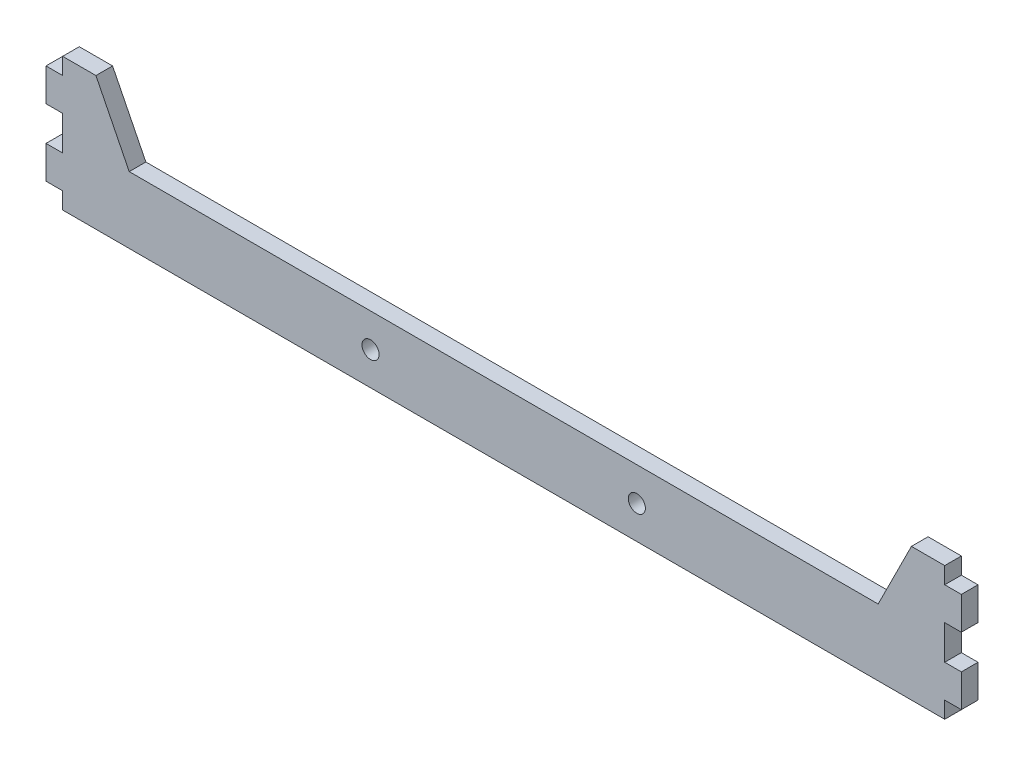
SolidWorks part; units mm, degrees
ref_plane "Front Plane" through (0, 0, 0) normal (0, 0, 1) x (1, 0, 0)
ref_plane "Top Plane" through (0, 0, 0) normal (0, 1, 0) x (1, 0, 0)
ref_plane "Right Plane" through (0, 0, 0) normal (1, 0, 0) x (0, 0, -1)
sketch "Sketch1" plane through (0, 0, 0) normal (0, 0, 1) x (1, 0, 0)
  line L0 (-168.275, -12.7) -> (-168.275, -6.35)
  line L1 (142.875, -12.7) -> (9.525, -12.7)
  line L2 (-142.875, -12.7) -> (-168.275, -12.7)
  line L3 (142.875, 12.7) -> (9.525, 12.7)
  line L4 (-168.275, 12.7) -> (-168.275, 19.25)
  line L5 (168.275, -12.7) -> (-168.275, 12.7) construction
  line L6 (168.275, 12.7) -> (-168.275, -12.7) construction
  line L7 (-168.275, 38.1) -> (-155.575, 38.1)
  line L8 (-155.575, 38.1) -> (-142.875, 12.7)
  line L9 (168.275, 0) -> (-168.275, 0) construction
  line L10 (-168.275, -6.35) -> (-174.625, -6.35)
  line L11 (-168.275, 31.75) -> (-174.625, 31.75)
  line L12 (168.275, -12.7) -> (168.275, -6.35)
  line L13 (0, 12.7) -> (0, -12.7) construction
  line L14 (-168.275, 19.25) -> (-174.625, 19.25)
  line L15 (-174.625, 31.75) -> (-174.625, 19.25)
  line L16 (-174.625, -6.35) -> (-174.625, 6.15)
  line L17 (-168.275, 6.15) -> (-174.625, 6.15)
  line L18 (-168.275, 6.15) -> (-168.275, 12.7)
  line L19 (-168.275, 31.75) -> (-168.275, 38.1)
  line L20 (168.275, -6.35) -> (174.625, -6.35)
  line L21 (174.625, -6.35) -> (174.625, 6.15)
  line L22 (168.275, 6.15) -> (174.625, 6.15)
  line L23 (168.275, 6.15) -> (168.275, 12.7)
  line L24 (168.275, 12.7) -> (168.275, 19.25)
  line L25 (174.625, 31.75) -> (174.625, 19.25)
  line L26 (168.275, 19.25) -> (174.625, 19.25)
  line L27 (168.275, 31.75) -> (174.625, 31.75)
  line L28 (168.275, 31.75) -> (168.275, 38.1)
  line L29 (168.275, 38.1) -> (155.575, 38.1)
  line L30 (155.575, 38.1) -> (142.875, 12.7)
  line L31 (142.875, -12.7) -> (168.275, -12.7)
  line L32 (-9.525, 12.7) -> (-142.875, 12.7)
  line L33 (-9.525, -12.7) -> (-142.875, -12.7)
  line L34 (-9.525, 12.7) -> (9.525, 12.7)
  line L35 (9.525, -12.7) -> (-9.525, -12.7)
  point P0 (0, 0)
  dimension "D1" = 25.4
  dimension "D2" = 336.55
  dimension "D3" = 25.4
  dimension "D4" = 6.35
  dimension "D5" = 12.5
  dimension "D6" = 6.35
  dimension "D7" = 25.4
extrude "Boss-Extrude1" add sketch "Sketch1" along normal blind 6.35
fillet "Fillet1" [suppressed] radius 2.54
hole_wizard "F (0.257) Diameter Hole1" positions "Sketch4" profile "Sketch3" hole size "F" standard "ANSI Inch" end condition through all
sketch "Sketch4" plane through (0, 0, 6.35) normal (0, 0, 1) x (1, 0, 0)
  line L0 (-174.625, -0.1) -> (174.625, -0.1) construction
  line L1 (-174.625, -6.35) -> (-174.625, 6.15) construction
  line L2 (174.625, -6.35) -> (174.625, 6.15) construction
  line L3 (0, -12.7) -> (0, 12.7) construction
  line L4 (168.275, -12.7) -> (-168.275, -12.7) construction
  line L5 (142.875, 12.7) -> (-142.875, 12.7) construction
  point P14 (-50.8, -0.1)
  point P18 (50.8, -0.1)
  dimension "D1" = 50.8
  dimension "D4" = 50.8
sketch "Sketch3" plane through (-50.8, -0.1, 6.35) normal (1, 0, 0) x (0, -1, 0)
  line L0 (0, 0) -> (0, 6.35)
  line L1 (0, 6.35) -> (3.2639, 6.35)
  line L2 (3.2639, 6.35) -> (3.2639, 0)
  line L5 (3.2639, 0) -> (0, 0)
  line L11 (0, -6.35) -> (0, 107.95) construction
  dimension "Thru Hole Dia." = 6.5278
  dimension "Thru Hole Depth" = 6.35
